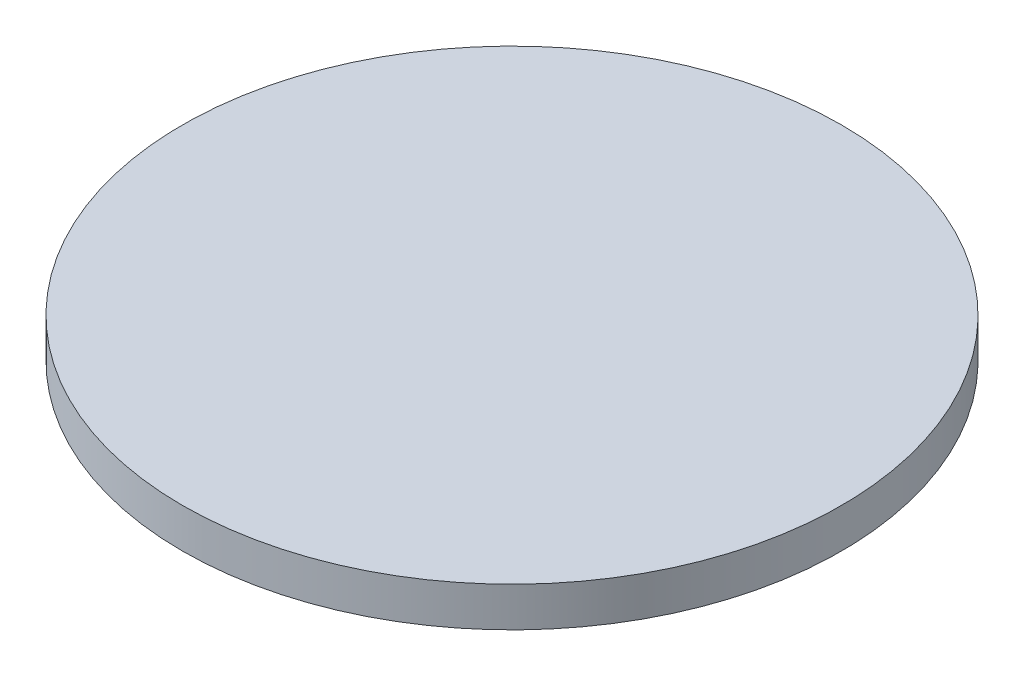
SolidWorks part; units mm, degrees
ref_plane "前视基准面" through (0, 0, 0) normal (0, 0, 1) x (1, 0, 0)
ref_plane "上视基准面" through (0, 0, 0) normal (0, 1, 0) x (1, 0, 0)
ref_plane "右视基准面" through (0, 0, 0) normal (1, 0, 0) x (0, 0, -1)
sketch "草图1" plane through (0, 0, 0) normal (0, 1, 0) x (1, 0, 0)
  circle A0 centre (0, 0) radius 125
  dimension "D1" = 250
extrude "凸台-拉伸1" add sketch "草图1" along normal blind 15
